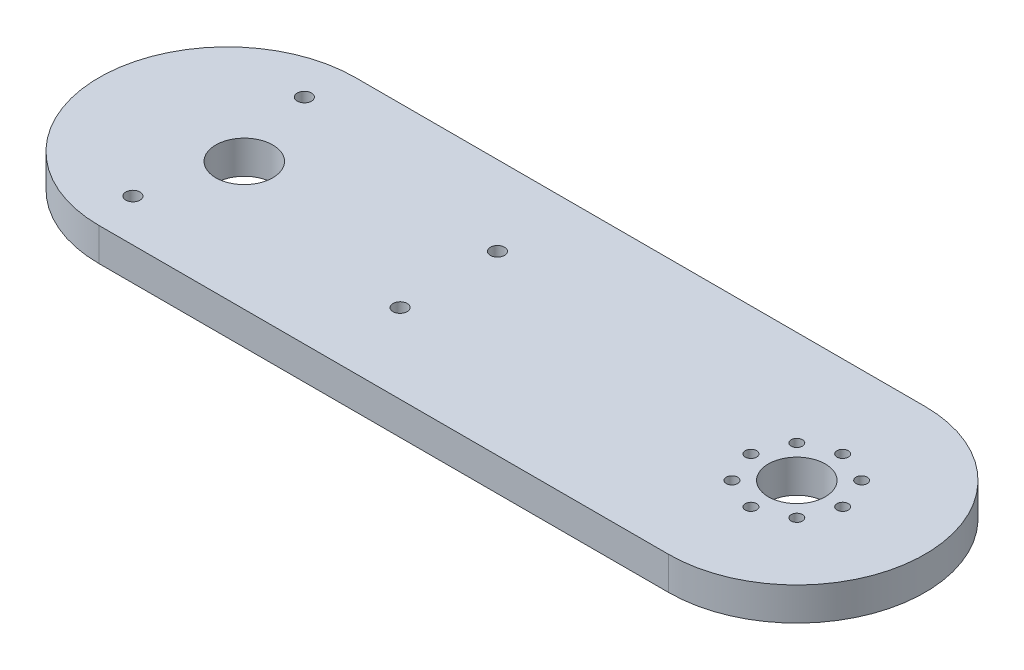
SolidWorks part; units mm, degrees
ref_plane "Front Plane" through (0, 0, 0) normal (0, 0, 1) x (1, 0, 0)
ref_plane "Top Plane" through (0, 0, 0) normal (0, 1, 0) x (1, 0, 0)
ref_plane "Right Plane" through (0, 0, 0) normal (1, 0, 0) x (0, 0, -1)
sketch "Sketch2" plane through (0, 0, 0) normal (0, 1, 0) x (1, 0, 0)
  line L0 (50, 0) -> (-50, 0) construction
  line L1 (50, -22.5) -> (-50, -22.5)
  line L2 (50, 22.5) -> (-50, 22.5)
  arc A0 (50, -22.5) -> (50, 22.5) centre (50, 0) ccw
  arc A1 (-50, 22.5) -> (-50, -22.5) centre (-50, 0) ccw
  point P2 (0, 0)
  dimension "D2" = 100
  dimension "D1" = 45
extrude "Boss-Extrude1" add sketch "Sketch2" along normal mid plane 5.8
sketch "Sketch3" plane through (0, 2.9, 0) normal (0, 1, 0) x (1, 0, 0)
  circle A1 centre (50, 0) radius 1.9176 construction
  arc A2 (50, -22.5) -> (50, 22.5) centre (50, 0) ccw construction
  circle A3 centre (41.95, 0) radius 0.99
  circle A17 centre (44.3078, 5.6922) radius 0.99
  circle A18 centre (50, 8.05) radius 0.99
  circle A19 centre (55.6922, 5.6922) radius 0.99
  circle A20 centre (58.05, 0) radius 0.99
  circle A21 centre (55.6922, -5.6922) radius 0.99
  circle A22 centre (50, -8.05) radius 0.99
  circle A23 centre (44.3078, -5.6922) radius 0.99
  dimension "D2" = 1.98
  dimension "D4" = 20.5824
  dimension "D1" = 8.05
  dimension "D3" = 8
extrude "Cut-Extrude1" cut sketch "Sketch3" against normal through all both and the other way through all
sketch "Sketch4" plane through (0, 2.9, 0) normal (0, 1, 0) x (1, 0, 0)
  circle A0 centre (50, 0) radius 5
  arc A1 (50, -22.5) -> (50, 22.5) centre (50, 0) ccw construction
  dimension "D1" = 10
extrude "Cut-Extrude2" cut sketch "Sketch4" against normal through all
sketch "Sketch5" plane through (0, 2.9, 0) normal (0, 1, 0) x (1, 0, 0)
  line L0 (0, 0) -> (-45.6257, 0) construction
  circle A0 centre (-51.5, -15.05) radius 1.25
  circle A1 centre (-51.5, 15.05) radius 1.25
  circle A2 centre (-11.1, 8.55) radius 1.25
  circle A3 centre (-11.1, -8.55) radius 1.25
  circle A4 centre (-47, 0) radius 5
  arc A5 (-50, 22.5) -> (-50, -22.5) centre (-50, 0) ccw construction
  dimension "D1" = 2.5
  dimension "D4" = 2.5
  dimension "D5" = 2.5
  dimension "D8" = 10
  dimension "D10" = 3
  dimension "D2" = 15.05
  dimension "D3" = 15.05
  dimension "D6" = 8.55
  dimension "D7" = 40.4
  dimension "D9" = 4.5
extrude "Cut-Extrude3" cut sketch "Sketch5" against normal through all both and the other way through all
